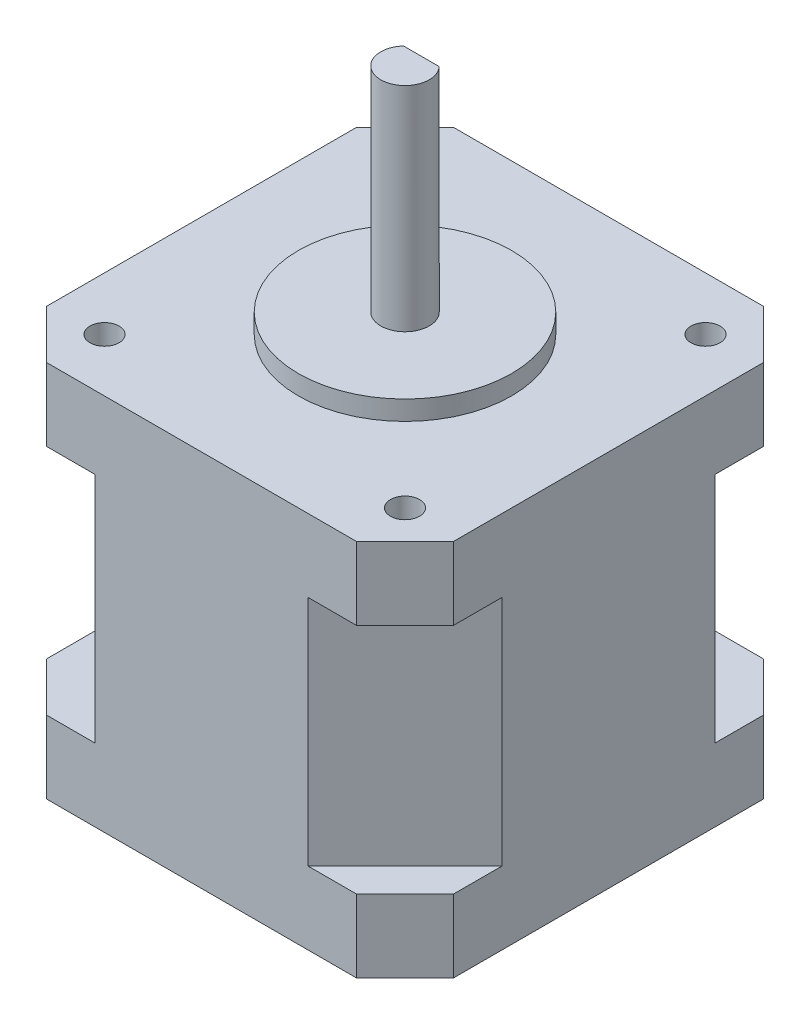
SolidWorks part; units mm, degrees
material "AISI 1020 钢，冷轧"
ref_plane "前视基准面" through (0, 0, 0) normal (0, 0, 1) x (1, 0, 0)
ref_plane "上视基准面" through (0, 0, 0) normal (0, 1, 0) x (1, 0, 0)
ref_plane "右视基准面" through (0, 0, 0) normal (1, 0, 0) x (0, 0, -1)
other "Configuration Table"
sketch "草图1" plane through (0, 0, 0) normal (0, 1, 0) x (1, 0, 0)
  line L0 (-21, 16) -> (-16, 21)
  line L1 (-16, -21) -> (16, -21)
  line L2 (-21, -16) -> (-21, 16)
  line L3 (-16, 21) -> (16, 21)
  line L4 (21, -16) -> (21, 16)
  line L5 (-21, -21) -> (21, 21) construction
  line L6 (-21, 21) -> (21, -21) construction
  line L7 (16, 21) -> (21, 16)
  line L8 (16, -21) -> (21, -16)
  line L9 (-21, -16) -> (-16, -21)
  point P0 (0, 0)
  dimension "D1" = 42
  dimension "D2" = 5
  dimension "D3" = 45
extrude "凸台-拉伸1" add sketch "草图1" against normal blind 7.5
sketch "草图2" plane through (0, -7.5, 0) normal (0, -1, 0) x (1, 0, 0)
  line L0 (-21, 11) -> (-11, 21)
  line L1 (-11, -21) -> (11, -21)
  line L2 (-21, -11) -> (-21, 11)
  line L3 (-11, 21) -> (11, 21)
  line L4 (21, -11) -> (21, 11)
  line L5 (-21, -21) -> (21, 21) construction
  line L6 (-21, 21) -> (21, -21) construction
  line L7 (11, 21) -> (21, 11)
  line L8 (11, -21) -> (21, -11)
  line L9 (-21, -11) -> (-11, -21)
  point P0 (0, 0)
  dimension "D1" = 42
  dimension "D2" = 42
extrude "凸台-拉伸2" add sketch "草图2" along normal blind 24
sketch "草图3" plane through (0, -31.5, 0) normal (0, -1, 0) x (1, 0, 0)
  line L0 (-21, 16) -> (-16, 21)
  line L1 (-16, -21) -> (16, -21)
  line L2 (-21, -16) -> (-21, 16)
  line L3 (-16, 21) -> (16, 21)
  line L4 (21, -16) -> (21, 16)
  line L5 (-21, -21) -> (21, 21) construction
  line L6 (-21, 21) -> (21, -21) construction
  line L7 (16, 21) -> (21, 16)
  line L8 (16, -21) -> (21, -16)
  line L9 (-21, -16) -> (-16, -21)
  point P0 (0, 0)
extrude "凸台-拉伸3" add sketch "草图3" along normal blind 7.5
sketch "草图4" plane through (0, 0, 0) normal (0, 1, 0) x (1, 0, 0)
  circle A0 centre (0, 0) radius 11
extrude "凸台-拉伸4" add sketch "草图4" along normal blind 2
sketch "草图5" plane through (0, 2, 0) normal (0, 1, 0) x (1, 0, 0)
  circle A0 centre (0, 0) radius 2.5
extrude "凸台-拉伸5" add sketch "草图5" along normal blind 22
sketch "草图6" plane through (0, 24, 0) normal (0, 1, 0) x (1, 0, 0)
  line L1 (-3.4944, 3.6478) -> (3.7113, 3.6478)
  line L2 (-3.4944, 3.6478) -> (-3.4944, 1.6935)
  line L3 (-3.4944, 1.6935) -> (3.7113, 1.6935)
  line L4 (3.7113, 3.6478) -> (3.7113, 1.6935)
extrude "切除-拉伸1" cut sketch "草图6" against normal blind 16
sketch "草图7" plane through (0, 0, 0) normal (0, 1, 0) x (1, 0, 0)
  line L0 (0, 0) -> (-35355.3391, 35355.3391) construction
  line L1 (0, -1000) -> (0, 49000) construction
  circle A0 centre (-15.5, 15.5) radius 1.5
  circle A1 centre (15.5, 15.5) radius 1.5
  circle A2 centre (15.5, -15.5) radius 1.5
  circle A3 centre (-15.5, -15.5) radius 1.5
  point P16 (0, 0)
  dimension "D1" = 15.5
  dimension "D2" = 4
extrude "切除-拉伸2" cut sketch "草图7" against normal blind 5
